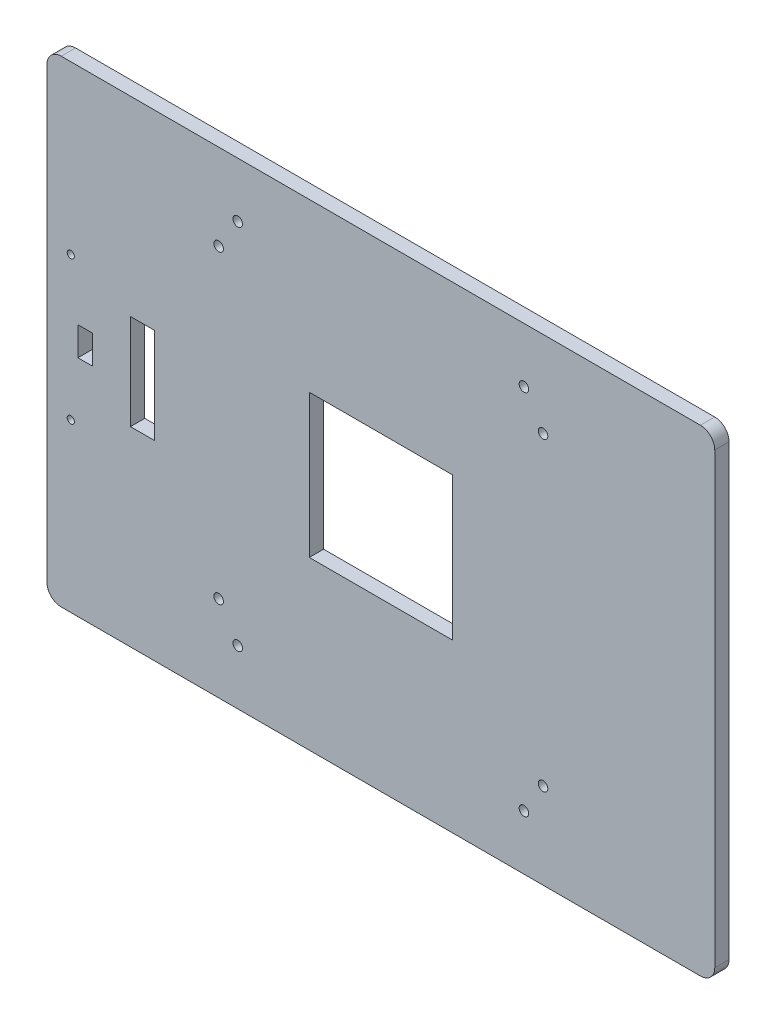
SolidWorks part; units mm, degrees
ref_plane "Front Plane" through (0, 0, 0) normal (0, 0, 1) x (1, 0, 0)
ref_plane "Top Plane" through (0, 0, 0) normal (0, 1, 0) x (1, 0, 0)
ref_plane "Right Plane" through (0, 0, 0) normal (1, 0, 0) x (0, 0, -1)
sketch "Sketch1" plane through (0, 0, 0) normal (0, 0, 1) x (1, 0, 0)
  line L1 (-70, 50) -> (70, 50)
  line L2 (-70, 50) -> (-70, -50)
  line L3 (-70, -50) -> (70, -50)
  line L4 (70, 50) -> (70, -50)
  line L5 (-70, 50) -> (70, -50) construction
  line L6 (-70, -50) -> (70, 50) construction
  point P0 (0, 0)
  dimension "D1" = 100
  dimension "D2" = 140
extrude "Boss-Extrude1" add sketch "Sketch1" along normal blind 3
sketch "Sketch2" plane through (0, 0, 3) normal (0, 0, 1) x (1, 0, 0)
  line L0 (0, 56.2301) -> (0, -56.8752) construction
  line L1 (-85.474, 38.5) -> (76.8728, 38.5) construction
  line L2 (81.8185, -38.5) -> (-96.4405, -38.5) construction
  line L3 (-70, -50) -> (70, -50) construction
  line L5 (70, 50) -> (-70, 50) construction
  circle A0 centre (30, 38.5) radius 1
  circle A1 centre (-30, 38.5) radius 1
  circle A2 centre (30, -38.5) radius 1
  circle A3 centre (-30, -38.5) radius 1
  dimension "D3" = 2
  dimension "D5" = 30
  dimension "D1" = 11.5
  dimension "D2" = 11.5
  dimension "D4" = 30
extrude "Cut-Extrude1" cut sketch "Sketch2" against normal blind 3
sketch "Sketch3" plane through (0, 0, 3) normal (0, 0, 1) x (1, 0, 0)
  line L0 (0, 55.0341) -> (0, -59.5575) construction
  line L1 (-87.1284, 0) -> (90.7902, 0) construction
  line L2 (-79.7792, 32) -> (80.4078, 32) construction
  line L3 (-79.7792, -32) -> (80.4078, -32) construction
  circle A0 centre (34, 32) radius 1
  circle A1 centre (34, -32) radius 1
  circle A2 centre (-34, 32) radius 1
  circle A3 centre (-34, -32) radius 1
  dimension "D7" = 2
  dimension "D1" = 32
  dimension "D2" = 32
  dimension "D3" = 34
  dimension "D4" = 34
  dimension "D5" = 34
  dimension "D6" = 34
extrude "Cut-Extrude2" cut sketch "Sketch3" against normal up to next
sketch "Sketch4" plane through (0, 0, 3) normal (0, 0, 1) x (1, 0, 0)
  line L0 (-65, 56.3265) -> (-65, -56.1111) construction
  line L1 (-15, 15) -> (15, 15)
  line L2 (-15, 15) -> (-15, -15)
  line L3 (-15, -15) -> (15, -15)
  line L4 (15, 15) -> (15, -15)
  line L5 (-15, 15) -> (15, -15) construction
  line L6 (-15, -15) -> (15, 15) construction
  line L7 (-70, 50) -> (-70, -50) construction
  line L8 (-90.7271, 0) -> (36.4562, 0) construction
  circle A0 centre (-65, 15) radius 0.75
  circle A1 centre (-65, -15) radius 0.75
  point P0 (0, 0)
  dimension "D5" = 1.5
  dimension "D1" = 30
  dimension "D2" = 30
  dimension "D3" = 5
  dimension "D4" = 30
extrude "Cut-Extrude3" cut sketch "Sketch4" against normal up to next
fillet "Fillet1" radius 3 4 edges at (70, -50, 1.5) (70, 50, 1.5) (-70, -50, 1.5) (-70, 50, 1.5)
sketch "Sketch5" plane through (0, 0, 3) normal (0, 0, 1) x (1, 0, 0)
  line L0 (-77.0996, 0) -> (-4.303, 0) construction
  line L1 (-70, 47) -> (-70, -47) construction
  line L2 (-52.5, 10) -> (-47.5, 10)
  line L3 (-52.5, 10) -> (-52.5, -10)
  line L4 (-52.5, -10) -> (-47.5, -10)
  line L5 (-47.5, 10) -> (-47.5, -10)
  line L6 (-52.5, 10) -> (-47.5, -10) construction
  line L7 (-52.5, -10) -> (-47.5, 10) construction
  point P3 (-50, 0)
  point P8 (-46.6441, -8.627)
  dimension "D1" = 5
  dimension "D2" = 20
  dimension "D3" = 20
extrude "Cut-Extrude4" cut sketch "Sketch5" against normal up to next
sketch "Sketch6" plane through (0, 0, 3) normal (0, 0, 1) x (1, 0, 0)
  line L0 (-78.3298, 0) -> (-8.9294, 0) construction
  line L1 (-70, 47) -> (-70, -47) construction
  line L2 (-63.5, 3) -> (-60.5, 3)
  line L3 (-63.5, 3) -> (-63.5, -3)
  line L4 (-63.5, -3) -> (-60.5, -3)
  line L5 (-60.5, 3) -> (-60.5, -3)
  line L6 (-63.5, 3) -> (-60.5, -3) construction
  line L7 (-63.5, -3) -> (-60.5, 3) construction
  point P3 (-62, 0)
  dimension "D1" = 8
  dimension "D2" = 3
  dimension "D3" = 6
extrude "Cut-Extrude5" cut sketch "Sketch6" against normal up to next
